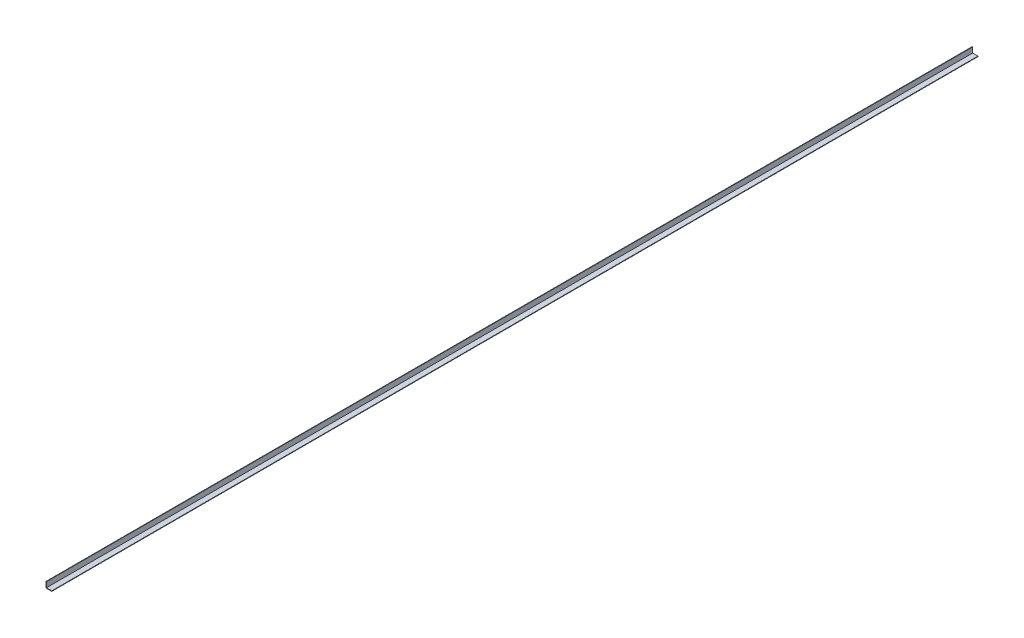
SolidWorks part; units mm, degrees
material "ASTM A36 Acero"
ref_plane "Alzado" through (0, 0, 0) normal (0, 0, 1) x (1, 0, 0)
ref_plane "Planta" through (0, 0, 0) normal (0, 1, 0) x (1, 0, 0)
ref_plane "Vista lateral" through (0, 0, 0) normal (1, 0, 0) x (0, 0, -1)
sketch "Croquis1" plane through (0, 0, 0) normal (0, 0, 1) x (1, 0, 0)
  line L0 (0, 38.1) -> (0, 0)
  line L1 (0, 0) -> (38.1, 0)
  line L2 (38.1, 0) -> (38.1, 3.18)
  line L3 (38.1, 3.18) -> (3.18, 3.18)
  line L4 (3.18, 3.18) -> (3.18, 38.1)
  line L5 (3.18, 38.1) -> (0, 38.1)
  dimension "D1" = 3.18
  dimension "D2" = 38.1
extrude "Saliente-Extruir1" add sketch "Croquis1" against normal blind 6100
